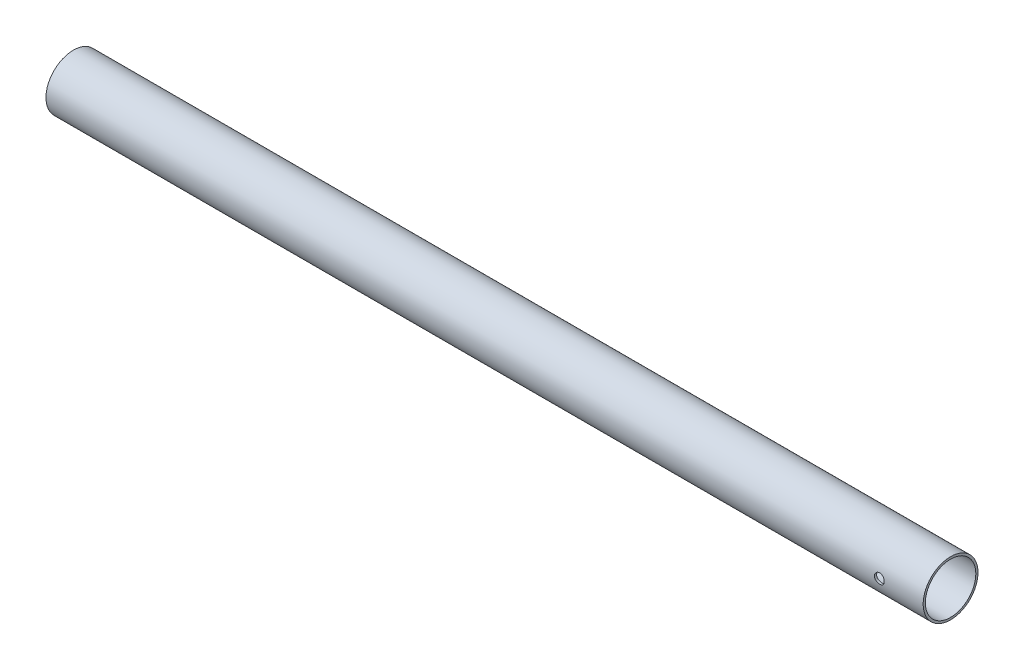
SolidWorks part; units mm, degrees
material "Thornel Mat VMA"
ref_plane "Front Plane" through (0, 0, 0) normal (0, 0, 1) x (1, 0, 0)
ref_plane "Top Plane" through (0, 0, 0) normal (0, 1, 0) x (1, 0, 0)
ref_plane "Right Plane" through (0, 0, 0) normal (1, 0, 0) x (0, 0, -1)
sketch "Sketch2" plane through (0, 0, 0) normal (1, 0, 0) x (0, 0, -1)
  circle A0 centre (0, 0) radius 12.5
  circle A1 centre (0, 0) radius 11.5
  dimension "D1" = 25
  dimension "D2" = 1
extrude "Boss-Extrude1" add sketch "Sketch2" along normal blind 400 contours A0
ref_plane "Plane1" through (0, 0, -12.5) normal (0, 0, -1) x (-1, 0, 0)
ref_plane "Plane2" through (0, 12.5, 0) normal (0, 1, 0) x (1, 0, 0)
hole_wizard "M4 Clearance Hole1" positions "Sketch7" profile "Sketch8" hole size "M4" standard "ANSI Metric" end condition through all
sketch "Sketch7" plane through (0, 0, -12.5) normal (0, 0, 1) x (1, 0, 0)
  line L0 (400, -12.5) -> (400, 12.5) construction
  line L2 (380, 0) -> (400, 0) construction
  point P0 (380, 0)
  dimension "D1" = 20
sketch "Sketch8" plane through (380, 0, -12.5) normal (1, 0, 0) x (0, 1, 0)
  line L0 (0, 0) -> (0, 25)
  line L1 (0, 25) -> (2.25, 25)
  line L2 (2.25, 25) -> (2.25, 0)
  line L5 (2.25, 0) -> (0, 0)
  line L11 (0, -6.35) -> (0, 107.95) construction
  dimension "Thru Hole Dia." = 4.5
  dimension "Thru Hole Depth" = 25
equation "\"tube_wall_thickness\"=1"
equation "\"D2@Sketch2\"=\"tube_wall_thickness\""
equation "\"tube_length\"=400"
equation "\"D1@Boss-Extrude1\"=\"tube_length\""
equation "\"centering_hole1_pos\"= 20"
equation "\"D1@Sketch7\"=\"centering_hole1_pos\""
equation "\"tube_diameter\"=25"
equation "\"D1@Sketch2\"=\"tube_diameter\""
